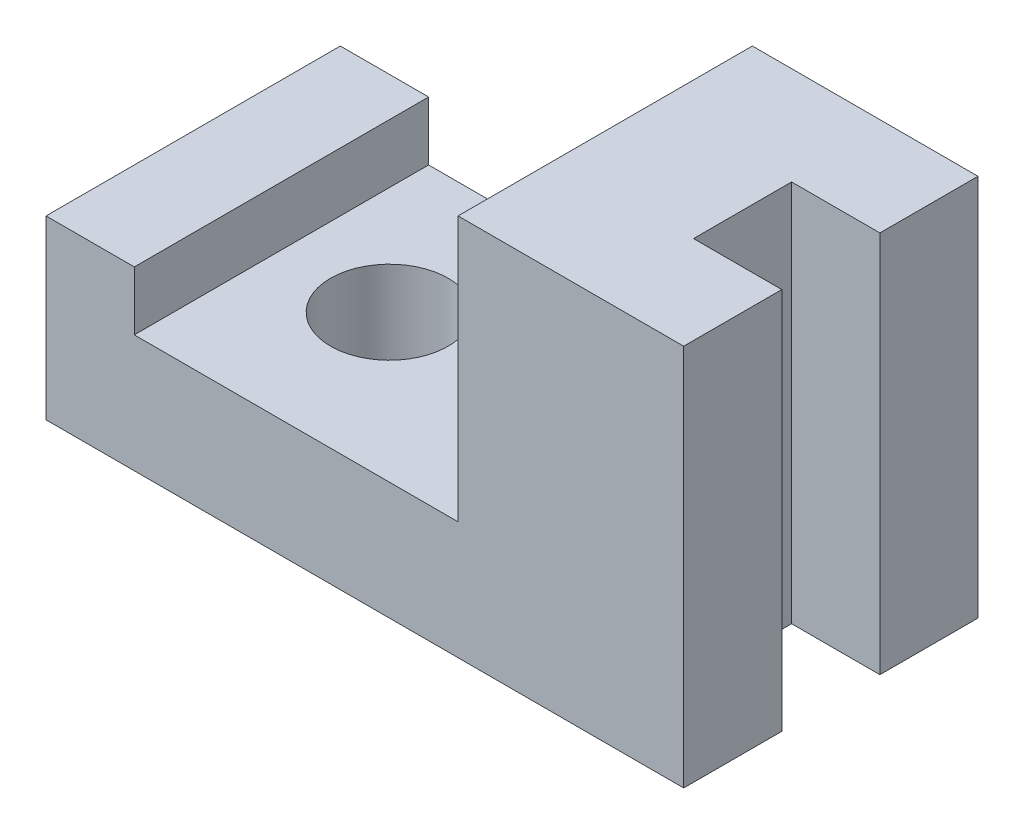
SolidWorks part; units mm, degrees
ref_plane "Front Plane" through (0, 0, 0) normal (0, 0, 1) x (1, 0, 0)
ref_plane "Top Plane" through (0, 0, 0) normal (0, 1, 0) x (1, 0, 0)
ref_plane "Right Plane" through (0, 0, 0) normal (1, 0, 0) x (0, 0, -1)
sketch "Sketch1" plane through (0, 0, 0) normal (0, 0, 1) x (1, 0, 0)
  line L1 (0, 0) -> (65, 0)
  line L2 (0, 0) -> (0, 39)
  line L3 (0, 39) -> (65, 39)
  line L4 (65, 0) -> (65, 39)
  dimension "D1" = 65
  dimension "D2" = 39
extrude "Boss-Extrude2" add sketch "Sketch1" along normal mid plane 30
sketch "Sketch3" plane through (65, 0, 0) normal (1, 0, 0) x (0, 0, -1)
  line L0 (5, 0) -> (-5, 0)
  line L1 (-15, 0) -> (15, 0) construction
  line L2 (-5, 0) -> (-5, 39)
  line L3 (-15, 39) -> (15, 39) construction
  line L4 (-5, 39) -> (5, 39)
  line L5 (5, 39) -> (5, 0)
  point P6 (0, 0)
  dimension "D1" = 10
extrude "Cut-Extrude1" cut sketch "Sketch3" against normal blind 9
sketch "Sketch5" plane through (0, 0, 15) normal (0, 0, 1) x (1, 0, 0)
  line L0 (42, 39) -> (42, 12)
  line L1 (65, 39) -> (0, 39) construction
  line L2 (42, 12) -> (9, 12)
  line L3 (9, 12) -> (9, 18)
  line L4 (9, 18) -> (0, 18)
  line L5 (0, 39) -> (0, 0) construction
  line L6 (0, 18) -> (0, 39)
  line L7 (0, 39) -> (42, 39)
  dimension "D1" = 9
  dimension "D2" = 6
  dimension "D3" = 21
  dimension "D4" = 42
extrude "Cut-Extrude2" cut sketch "Sketch5" against normal through all both and the other way through all
sketch "Sketch6" plane through (0, 12, 0) normal (0, 1, 0) x (1, 0, 0)
  line L0 (9, 15) -> (9, -15) construction
  circle A0 centre (20, 0) radius 6
  dimension "D1" = 12
  dimension "D2" = 11
extrude "Cut-Extrude3" cut sketch "Sketch6" against normal through all both
